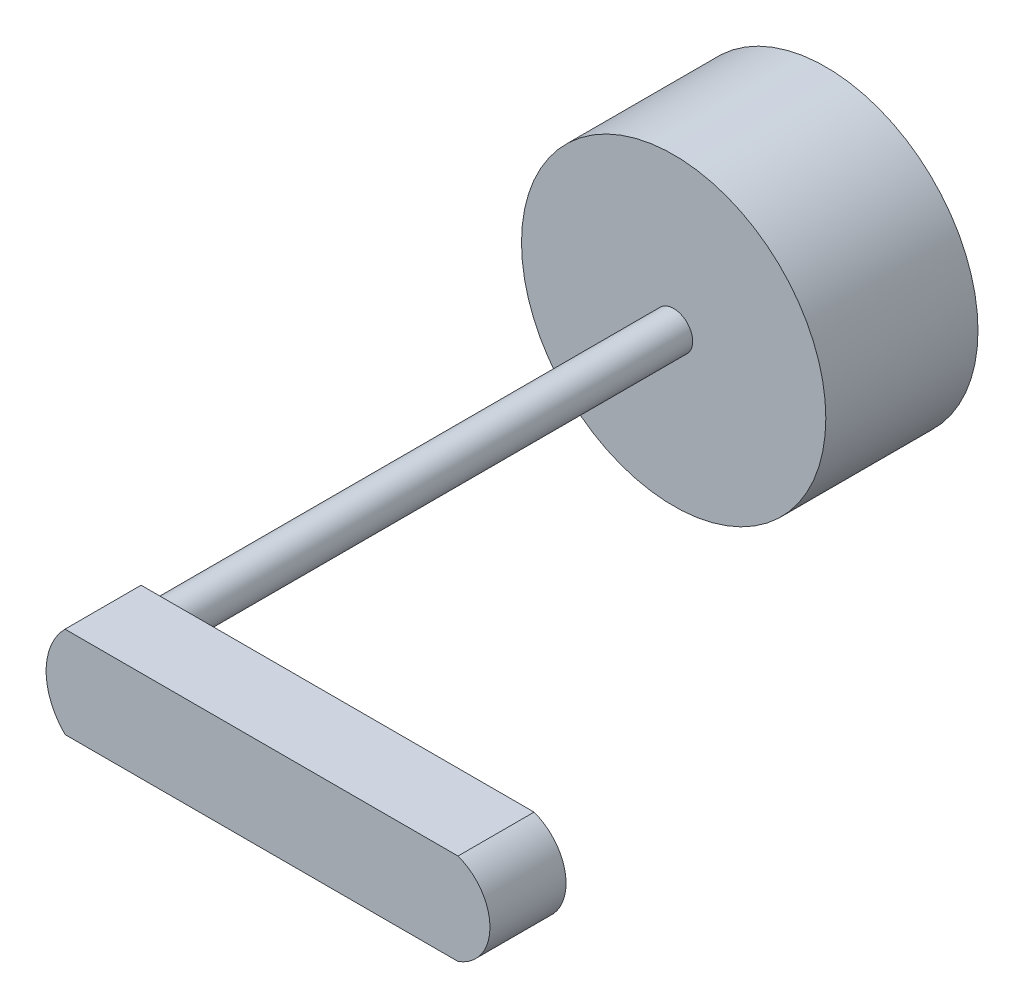
SolidWorks part; units mm, degrees
ref_plane "Спереди" through (0, 0, 0) normal (0, 0, 1) x (1, 0, 0)
ref_plane "Сверху" through (0, 0, 0) normal (0, 1, 0) x (1, 0, 0)
ref_plane "Справа" through (0, 0, 0) normal (1, 0, 0) x (0, 0, -1)
sketch "Эскиз1" plane through (0, 0, 0) normal (0, 0, 1) x (1, 0, 0)
  circle A0 centre (0, 0) radius 10
  dimension "D1" = 20
extrude "Бобышка-Вытянуть1" add sketch "Эскиз1" along normal blind 10 contours A0
sketch "Эскиз2" plane through (0, 0, 10) normal (0, 0, 1) x (1, 0, 0)
  circle A0 centre (0, 0) radius 1.25
  dimension "D1" = 2.5
extrude "Бобышка-Вытянуть2" add sketch "Эскиз2" along normal blind 40 contours A0
sketch "Эскиз3" plane through (0, 0, 50) normal (0, 0, 1) x (1, 0, 0)
  line L0 (0, 3) -> (25.8271, 3)
  line L1 (0, -3) -> (25.8271, -3)
  circle A4 centre (0, 0) radius 1.25 construction
  arc A5 (25.8271, 3) -> (25.8271, -3) centre (24.7355, 0) cw
  arc A6 (0, 3) -> (0, -3) centre (3, 0) ccw
  dimension "D1" = 3
  dimension "D2" = 3
extrude "Бобышка-Вытянуть3" add sketch "Эскиз3" against normal blind 5
